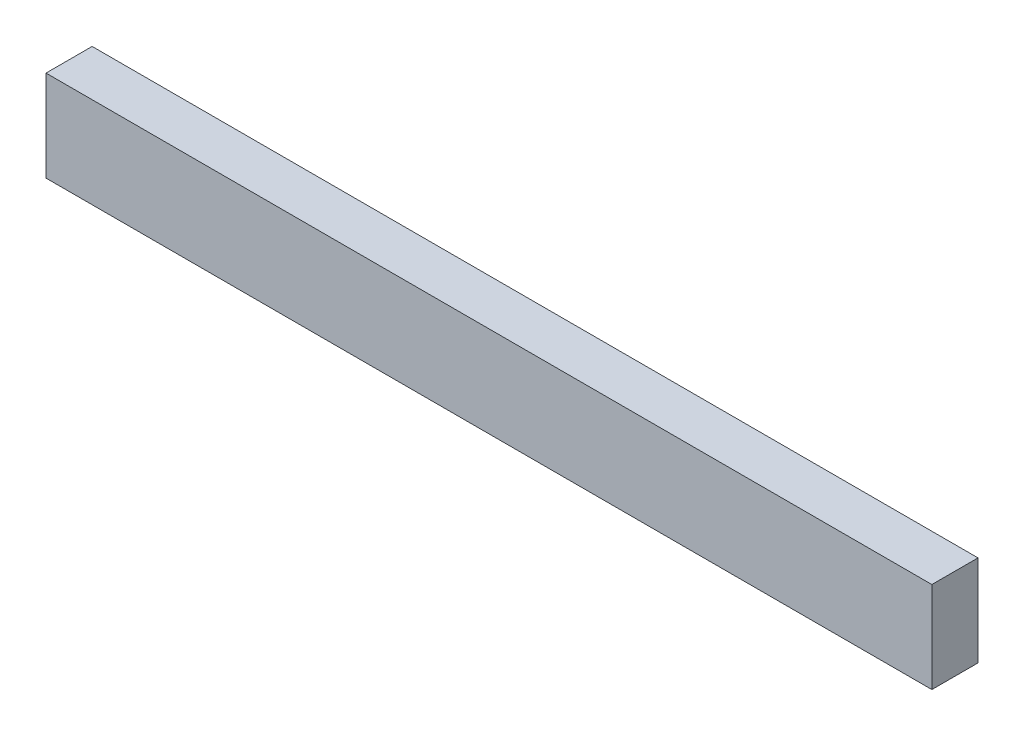
SolidWorks part; units mm, degrees
ref_plane "Přední rovina" through (0, 0, 0) normal (0, 0, 1) x (1, 0, 0)
ref_plane "Horní rovina" through (0, 0, 0) normal (0, 1, 0) x (1, 0, 0)
ref_plane "Pravá rovina" through (0, 0, 0) normal (1, 0, 0) x (0, 0, -1)
sketch "Skica1" plane through (0, 0, 0) normal (0, 0, 1) x (1, 0, 0)
  line L1 (-24, 2.465) -> (24, 2.465)
  line L2 (-24, 2.465) -> (-24, -2.465)
  line L3 (-24, -2.465) -> (24, -2.465)
  line L4 (24, 2.465) -> (24, -2.465)
  line L5 (-24, 2.465) -> (24, -2.465) construction
  line L6 (-24, -2.465) -> (24, 2.465) construction
  point P0 (0, 0)
  dimension "D1" = 48
  dimension "D2" = 4.93
extrude "Přidat vysunutím1" add sketch "Skica1" along normal blind 2.5
